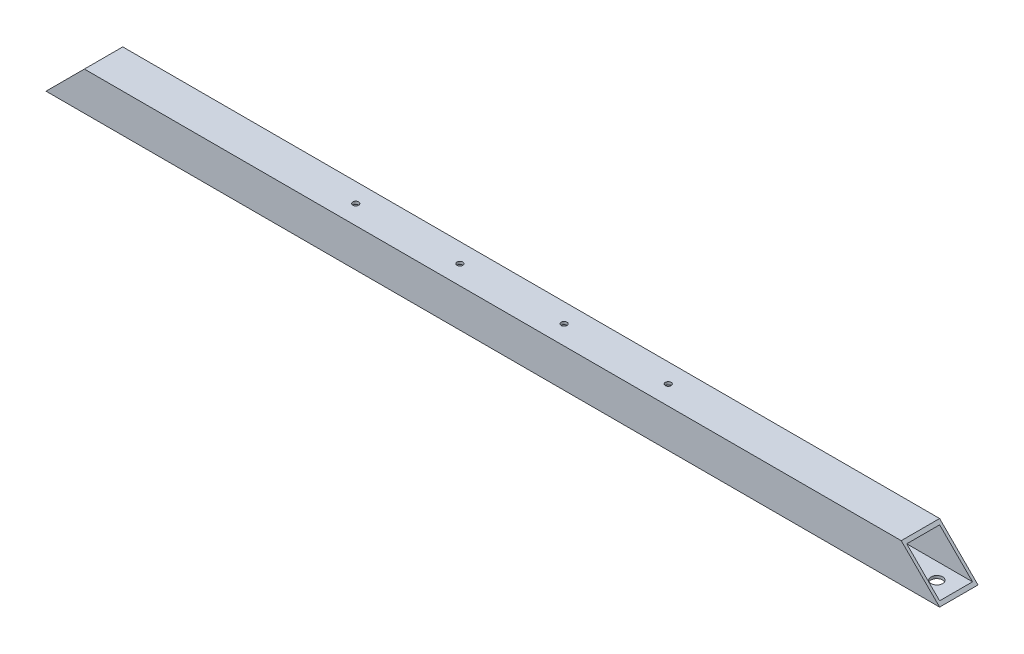
SolidWorks part; units mm, degrees
material "6061 Alloy"
ref_plane "Front Plane" through (0, 0, 0) normal (0, 0, 1) x (1, 0, 0)
ref_plane "Top Plane" through (0, 0, 0) normal (0, 1, 0) x (1, 0, 0)
ref_plane "Right Plane" through (0, 0, 0) normal (1, 0, 0) x (0, 0, -1)
sketch "Sketch1" plane through (0, 0, 0) normal (1, 0, 0) x (0, 0, -1)
  line L0 (19.05, -19.05) -> (19.05, 19.05)
  line L1 (-22.225, -22.225) -> (22.225, -22.225)
  line L2 (-22.225, -22.225) -> (-22.225, 22.225)
  line L3 (-22.225, 22.225) -> (22.225, 22.225)
  line L4 (22.225, -22.225) -> (22.225, 22.225)
  line L5 (-22.225, -22.225) -> (22.225, 22.225) construction
  line L6 (-22.225, 22.225) -> (22.225, -22.225) construction
  line L7 (-19.05, 19.05) -> (19.05, 19.05)
  line L8 (-19.05, -19.05) -> (-19.05, 19.05)
  line L9 (-19.05, -19.05) -> (19.05, -19.05)
  point P0 (0, 0)
  dimension "D1" = 44.45
  dimension "D2" = 3.175
extrude "Boss-Extrude1" add sketch "Sketch1" along normal blind 1035.05
sketch "Sketch2" plane through (0, 0, 22.225) normal (0, 0, 1) x (1, 0, 0)
  line L0 (517.525, 22.225) -> (517.525, -22.225) construction
  line L1 (1035.05, 22.225) -> (0, 22.225) construction
  line L2 (1035.05, -22.225) -> (0, -22.225) construction
  line L3 (0, 22.225) -> (0, -22.225)
  line L4 (0, -22.225) -> (44.45, 22.225)
  line L5 (44.45, 22.225) -> (0, 22.225)
  line L6 (990.6, 22.225) -> (1035.05, 22.225)
  line L7 (1035.05, -22.225) -> (990.6, 22.225)
  line L8 (1035.05, 22.225) -> (1035.05, -22.225)
extrude "Cut-Extrude1" cut sketch "Sketch2" against normal through all
hole_wizard "1/2 Clearance Hole1" positions "Sketch3" profile "Sketch4" hole size "1/2" standard "ANSI Inch" end condition through all
sketch "Sketch3" plane through (0, -22.225, 0) normal (0, -1, 0) x (-1, 0, 0)
  line L0 (-517.525, 22.225) -> (-517.525, -22.225) construction
  line L1 (-1035.05, 22.225) -> (0, 22.225) construction
  line L2 (-1035.05, -22.225) -> (0, -22.225) construction
  line L3 (0, 0) -> (-1035.05, 0) construction
  line L4 (-1035.05, -22.225) -> (-1035.05, 22.225) construction
  point P0 (-25.4, 0)
  point P10 (-1009.65, 0)
  dimension "D1" = 984.25
sketch "Sketch4" plane through (25.4, -22.225, 0) normal (1, 0, 0) x (0, 0, -1)
  line L0 (0, 0) -> (0, 44.45)
  line L1 (0, 44.45) -> (6.7462, 44.45)
  line L2 (6.7462, 44.45) -> (6.7462, 0)
  line L5 (6.7462, 0) -> (0, 0)
  line L11 (0, -6.35) -> (0, 107.95) construction
  dimension "Thru Hole Dia." = 13.4925
  dimension "Thru Hole Depth" = 44.45
hole_wizard "1/4 Clearance Hole1" positions "Sketch6" profile "Sketch7" hole size "1/4" standard "ANSI Inch" end condition through all
sketch "Sketch6" plane through (0, 22.225, 0) normal (0, 1, 0) x (1, 0, 0)
  line L0 (517.525, -22.225) -> (517.525, 22.225) construction
  line L1 (990.6, -22.225) -> (44.45, -22.225) construction
  line L2 (990.6, 22.225) -> (44.45, 22.225) construction
  line L3 (990.6, 0) -> (44.45, 0) construction
  line L4 (990.6, 22.225) -> (990.6, -22.225) construction
  line L5 (44.45, 22.225) -> (44.45, -22.225) construction
  point P0 (336.55, 0)
  point P2 (457.2, 0)
  point P12 (577.85, 0)
  point P13 (698.5, 0)
  dimension "D1" = 120.65
  dimension "D2" = 120.65
sketch "Sketch7" plane through (336.55, 22.225, 0) normal (1, 0, 0) x (0, 0, 1)
  line L0 (0, 0) -> (0, 44.45)
  line L1 (0, 44.45) -> (3.3782, 44.45)
  line L2 (3.3782, 44.45) -> (3.3782, 0)
  line L5 (3.3782, 0) -> (0, 0)
  line L11 (0, -6.35) -> (0, 107.95) construction
  dimension "Thru Hole Dia." = 6.7564
  dimension "Thru Hole Depth" = 44.45
